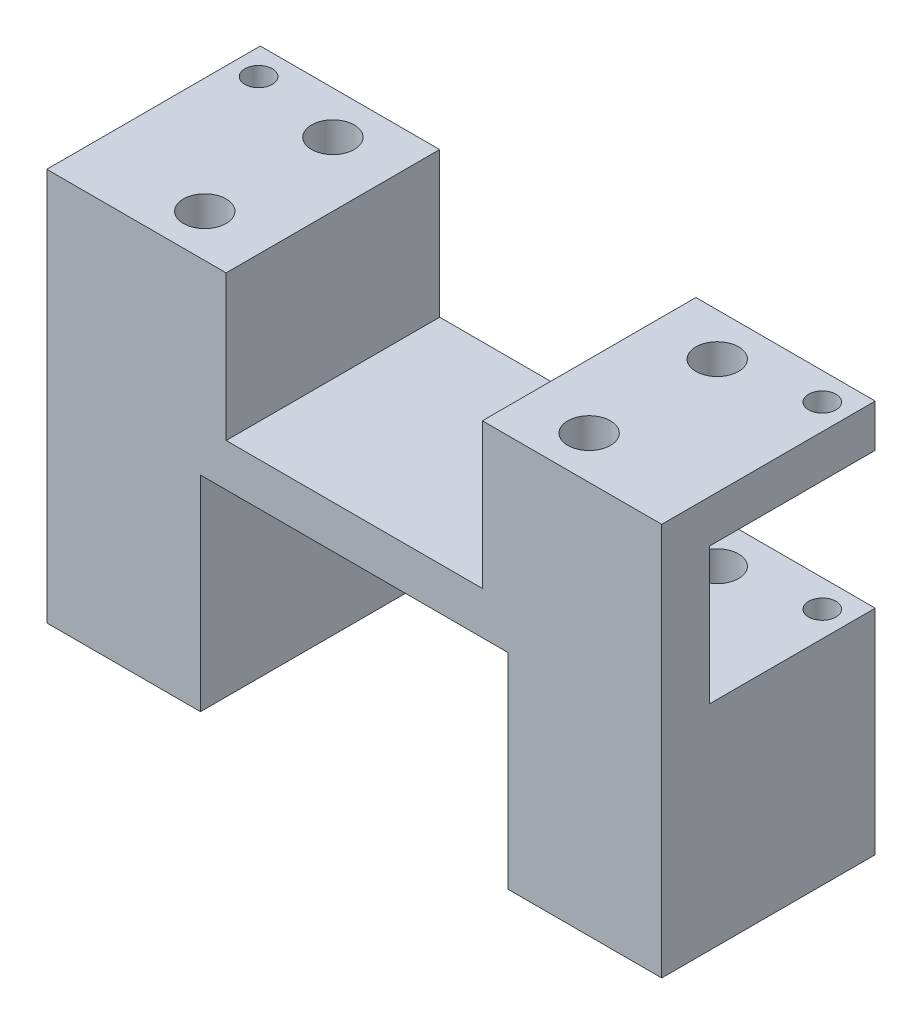
SolidWorks part; units mm, degrees
ref_plane "Front Plane" through (0, 0, 0) normal (0, 0, 1) x (1, 0, 0)
ref_plane "Top Plane" through (0, 0, 0) normal (0, 1, 0) x (1, 0, 0)
ref_plane "Right Plane" through (0, 0, 0) normal (1, 0, 0) x (0, 0, -1)
sketch "Sketch6" plane through (0, 0, 0) normal (0, 1, 0) x (1, 0, 0)
  line L1 (-36, 12.5) -> (36, 12.5)
  line L2 (-36, 12.5) -> (-36, -12.5)
  line L3 (-36, -12.5) -> (36, -12.5)
  line L4 (36, 12.5) -> (36, -12.5)
  line L5 (-36, 12.5) -> (36, -12.5) construction
  line L6 (-36, -12.5) -> (36, 12.5) construction
  point P0 (0, 0)
  dimension "D1" = 72
  dimension "D2" = 25
extrude "Boss-Extrude2" add sketch "Sketch6" along normal blind 46
sketch "Sketch9" plane through (0, 46, 0) normal (0, 1, 0) x (1, 0, 0)
  line L0 (0, 0) -> (0, 12.5) construction
  line L1 (36, 12.5) -> (-36, 12.5) construction
  line L2 (36, -12.5) -> (36, 12.5) construction
  circle A0 centre (-33, 9.3) radius 1.6
  circle A1 centre (33, 9.3) radius 1.6
  dimension "D1" = 3.2
  dimension "D2" = 3
  dimension "D3" = 3.2
extrude "Cut-Extrude3" cut sketch "Sketch9" against normal blind 35
hole_wizard "Top Screw Holes" positions "Sketch10" profile "Sketch11" hole size "Ø5.0" standard "ANSI Metric" end condition through all
sketch "Sketch10" plane through (0, 46, 0) normal (0, 1, 0) x (1, 0, 0)
  line L0 (0, 0) -> (0, -12.5) construction
  line L1 (-36, -12.5) -> (36, -12.5) construction
  line L3 (36, 12.5) -> (-36, 12.5) construction
  line L4 (0, 0) -> (0, 12.5) construction
  point P0 (-22.5, -7.5)
  point P11 (22.5, -7.5)
  point P30 (-22.5, 7.5)
  point P31 (22.5, 7.5)
  dimension "D1" = 45
  dimension "D2" = 20
  dimension "D3" = 2
sketch "Sketch11" plane through (-22.5, 46, 7.5) normal (1, 0, 0) x (0, 0, 1)
  line L0 (0, 0) -> (0, 46)
  line L1 (0, 46) -> (2.5, 46)
  line L2 (2.5, 46) -> (2.5, 0)
  line L5 (2.5, 0) -> (0, 0)
  line L11 (0, -6.35) -> (0, 107.95) construction
  dimension "Thru Hole Dia." = 5
  dimension "Thru Hole Depth" = 46
sketch "Sketch12" plane through (0, 0, 12.5) normal (0, 0, 1) x (1, 0, 0)
  line L0 (0, 0) -> (0, 46) construction
  line L1 (-36, 0) -> (36, 0) construction
  line L2 (-36, 46) -> (36, 46) construction
  line L3 (-18, 24) -> (-18, 0)
  line L4 (-18, 24) -> (18, 24)
  line L5 (-18, 0) -> (18, 0)
  line L6 (18, 24) -> (18, 0)
  line L7 (-18, 24) -> (18, 0) construction
  line L8 (-18, 0) -> (18, 24) construction
  point P7 (0, 12)
  dimension "D1" = 36
  dimension "D2" = 0
  dimension "D3" = 24
extrude "Cut-Extrude4" cut sketch "Sketch12" against normal through all
sketch "Sketch13" plane through (0, 46, 0) normal (0, 1, 0) x (1, 0, 0)
  line L0 (36, 12.5) -> (-36, 12.5) construction
  line L1 (15, -12.5) -> (-15, -12.5)
  line L2 (15, -12.5) -> (15, 12.5)
  line L3 (15, 12.5) -> (-15, 12.5)
  line L4 (-15, -12.5) -> (-15, 12.5)
  line L5 (15, -12.5) -> (-15, 12.5) construction
  line L6 (15, 12.5) -> (-15, -12.5) construction
  point P0 (0, 0)
  dimension "D1" = 30
extrude "Cut-Extrude5" cut sketch "Sketch13" against normal blind 17
sketch "Sketch14" plane through (0, 0, 0) normal (0, 1, 0) x (1, 0, 0)
  circle A0 centre (-33, 9.3) radius 16.5
  circle A1 centre (33, 9.3) radius 16.5
  dimension "D1" = 33
  dimension "D2" = 33
extrude "Cut-Extrude6" cut sketch "Sketch14" along normal blind 16 from offset 25
